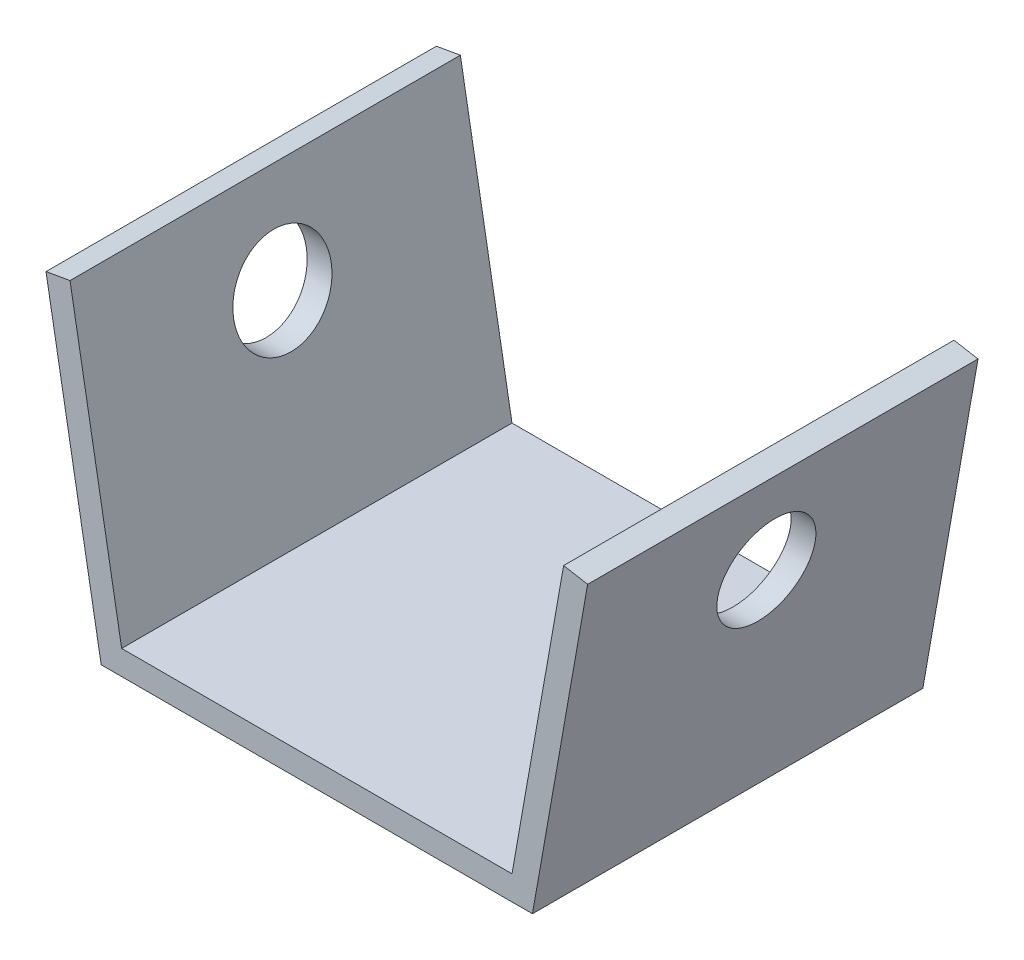
SolidWorks part; units mm, degrees
ref_plane "Front Plane" through (0, 0, 0) normal (0, 0, 1) x (1, 0, 0)
ref_plane "Top Plane" through (0, 0, 0) normal (0, 1, 0) x (1, 0, 0)
ref_plane "Right Plane" through (0, 0, 0) normal (1, 0, 0) x (0, 0, -1)
sketch "Sketch1" plane through (0, 0, 0) normal (0, 0, 1) x (1, 0, 0)
  line L0 (-25.4, 0) -> (25.4, 0)
  line L1 (25.4, 0) -> (32.1181, 38.1)
  line L2 (-25.4, 0) -> (-32.1181, 38.1)
  line L3 (28.0641, -3.175) -> (35.2448, 37.5487)
  line L4 (-28.0641, -3.175) -> (28.0641, -3.175)
  line L5 (-28.0641, -3.175) -> (-35.2448, 37.5487)
  line L6 (-35.2448, 37.5487) -> (-32.1181, 38.1)
  line L7 (32.1181, 38.1) -> (35.2448, 37.5487)
  dimension "D1" = 50.8
  dimension "D2" = 38.1
  dimension "D3" = 100
  dimension "D4" = 100
  dimension "D5" = 3.175
extrude "Boss-Extrude1" add sketch "Sketch1" along normal mid plane 50.8
sketch "Sketch2" plane through (0, 0, 0) normal (1, 0, 0) x (0, 0, -1)
  circle A0 centre (0, 25.4) radius 6.35
  dimension "D1" = 12.7
  dimension "D2" = 25.4
extrude "Cut-Extrude1" cut sketch "Sketch2" against normal through all and the other way through all
ref_plane "Plane3" through (19.05, 0, 0) normal (1, 0, 0) x (0, 0, -1)
